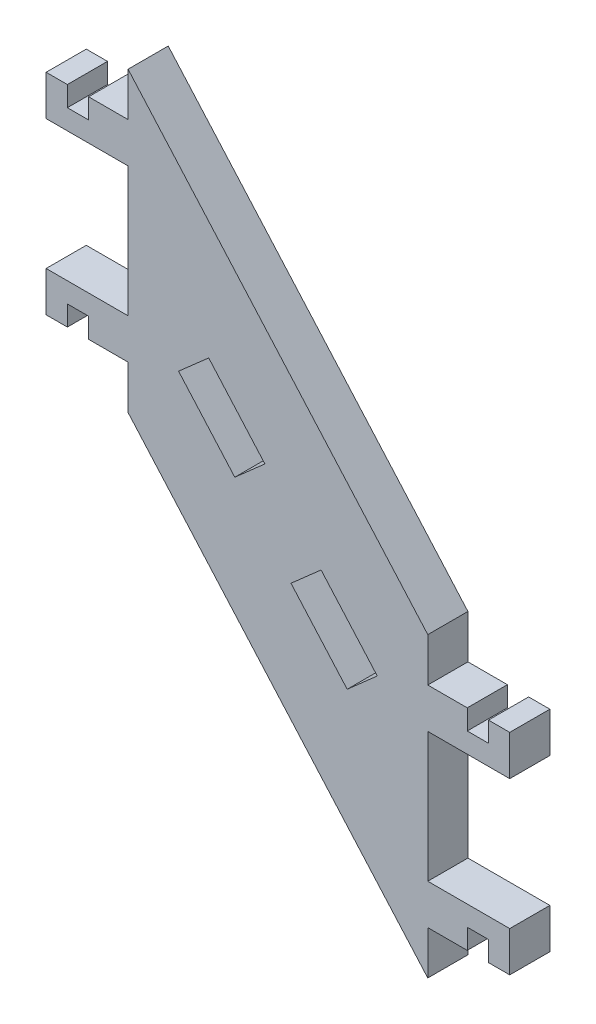
SolidWorks part; units mm, degrees
ref_plane "Front Plane" through (0, 0, 0) normal (0, 0, 1) x (1, 0, 0)
ref_plane "Top Plane" through (0, 0, 0) normal (0, 1, 0) x (1, 0, 0)
ref_plane "Right Plane" through (0, 0, 0) normal (1, 0, 0) x (0, 0, -1)
sketch "Sketch1" plane through (0, 0, 0) normal (0, 0, 1) x (1, 0, 0)
  line L0 (-44.8, 73.025) -> (-44.8, 66.5)
  line L1 (-44.8, 28.575) -> (0, -22.225)
  line L2 (0, -22.225) -> (0, -15.7)
  line L3 (0, 22.225) -> (-44.8, 73.025)
  line L4 (-44.8, 66.5) -> (-50.7, 66.5)
  line L5 (-57.05, 66.5) -> (-57.05, 60.5)
  line L6 (-57.05, 60.5) -> (-44.8, 60.5)
  line L7 (-44.8, 73.025) -> (-50.7, 73.025) construction
  line L8 (-50.7, 73.025) -> (-50.7, 28.575) construction
  line L9 (-50.7, 28.575) -> (-44.8, 28.575) construction
  line L10 (-53.875, 66.5) -> (-53.875, 63.5)
  line L11 (-53.875, 63.5) -> (-50.7, 63.5)
  line L12 (-50.7, 63.5) -> (-50.7, 66.5)
  line L13 (-53.875, 66.5) -> (-57.05, 66.5)
  line L14 (-44.8, 50.8) -> (-64.1486, 50.8) construction
  line L15 (-44.8, 35.1) -> (-50.7, 35.1)
  line L16 (-57.05, 41.1) -> (-44.8, 41.1)
  line L17 (-53.875, 35.1) -> (-57.05, 35.1)
  line L18 (-50.7, 38.1) -> (-50.7, 35.1)
  line L19 (-53.875, 38.1) -> (-50.7, 38.1)
  line L20 (-53.875, 35.1) -> (-53.875, 38.1)
  line L21 (-57.05, 35.1) -> (-57.05, 41.1)
  line L22 (-57.05, 63.5) -> (-50.7, 63.5) construction
  line L23 (0, 0) -> (19.05, 0) construction
  line L24 (0, 9.7) -> (12.25, 9.7)
  line L25 (12.25, 9.7) -> (12.25, 15.7)
  line L26 (12.25, 15.7) -> (9.075, 15.7)
  line L27 (9.075, 15.7) -> (9.075, 12.7)
  line L28 (9.075, 12.7) -> (5.9, 12.7)
  line L29 (5.9, 12.7) -> (5.9, 15.7)
  line L30 (5.9, 15.7) -> (0, 15.7)
  line L31 (5.9, -15.7) -> (0, -15.7)
  line L32 (5.9, -12.7) -> (5.9, -15.7)
  line L33 (9.075, -12.7) -> (5.9, -12.7)
  line L34 (9.075, -15.7) -> (9.075, -12.7)
  line L35 (12.25, -15.7) -> (9.075, -15.7)
  line L36 (12.25, -9.7) -> (12.25, -15.7)
  line L37 (0, -9.7) -> (12.25, -9.7)
  line L38 (0, 22.225) -> (5.9, 22.225) construction
  line L39 (5.9, 22.225) -> (5.9, -22.225) construction
  line L40 (5.9, -22.225) -> (0, -22.225) construction
  line L41 (-44.8, 35.1) -> (-44.8, 41.1) construction
  line L42 (-44.8, 60.5) -> (-44.8, 41.1)
  line L43 (-44.8, 35.1) -> (-44.8, 28.575)
  line L44 (0, 15.7) -> (0, 22.225)
  line L45 (0, -9.7) -> (0, 9.7)
  line L46 (-50.8, -31.2865) -> (-44.8, -31.2865) construction
  line L47 (-50.8, -31.2865) -> (-50.8, 31.2865) construction
  line L48 (-50.8, 31.2865) -> (-44.8, 31.2865) construction
  line L49 (-44.8, -31.2865) -> (-44.8, 31.2865) construction
  line L50 (-50.8, -31.2865) -> (-44.8, 31.2865) construction
  line L51 (-50.8, 31.2865) -> (-44.8, -31.2865) construction
  line L52 (0, -31.2865) -> (6, -31.2865) construction
  line L53 (0, -31.2865) -> (0, 31.2865) construction
  line L54 (0, 31.2865) -> (6, 31.2865) construction
  line L55 (6, -31.2865) -> (6, 31.2865) construction
  line L56 (0, -31.2865) -> (6, 31.2865) construction
  line L57 (0, 31.2865) -> (6, -31.2865) construction
  line L58 (-44.8, 60.5) -> (-44.8, 66.5) construction
  point P25 (-47.8, 0)
  point P37 (0, 0)
  point P53 (3, 0)
  point P58 (-44.8, 38.1)
  point P59 (-44.8, 63.5)
  point P60 (12.25, 12.7)
  point P61 (12.25, -12.7)
  dimension "D4" = 5.9
  dimension "D5" = 3.175
  dimension "D6" = 6
  dimension "D8" = 44.45
  dimension "D10" = 6
  dimension "D11" = 5.9
  dimension "D12" = 3.175
  dimension "D13" = 31.4
  dimension "D14" = 3.175
  dimension "D9" = 3.175
  dimension "D18" = 3.175
  dimension "D19" = 6
  dimension "D20" = 6
  dimension "D21" = 50.8
  dimension "D7" = 25.4
  dimension "D3" = 25.4
  dimension "D15" = 3
  dimension "D16" = 3
  dimension "D17" = 50.8
extrude "Profile" add sketch "Sketch1" along normal blind 6 contours L1 L2 L31 L32 L33 L34 L35 L36 L37 L45 L24 L25 L26 L27 L28 L29 L30 L44 L3 L0 L4 L12 L11 L10 L13 L5 L6 L42 L16 L21 L17 L20 L19 L18 L15 L43
sketch "Sketch2" plane through (0, 0, 6) normal (0, 0, 1) x (1, 0, 0)
  line L0 (-44.8, 50.8) -> (0, 0) construction
  line L1 (-44.8, 60.5) -> (-44.8, 41.1) construction
  line L2 (-32.7501, 41.672) -> (-37.2502, 37.7034)
  line L3 (-37.2502, 37.7034) -> (-28.8501, 28.1783)
  line L4 (-28.8501, 28.1783) -> (-24.35, 32.1468)
  line L5 (-24.35, 32.1468) -> (-32.7501, 41.672)
  line L6 (-33.4253, 15.6769) -> (-11.3747, 35.1231) construction
  line L7 (0, 22.225) -> (-44.8, 73.025) construction
  line L8 (-15.9499, 22.6217) -> (-7.5498, 13.0966)
  line L9 (-20.45, 18.6532) -> (-15.9499, 22.6217)
  line L10 (-12.0499, 9.128) -> (-20.45, 18.6532)
  line L11 (-7.5498, 13.0966) -> (-12.0499, 9.128)
  line L12 (-37.2502, 37.7034) -> (-24.35, 32.1468) construction
  point P7 (-35.0002, 39.6877)
  point P14 (-22.4, 25.4)
  point P21 (-30.8001, 34.9251)
  dimension "D1" = 6
  dimension "D2" = 12.7
  dimension "D3" = 12.7
extrude "Cut-Extrude1" cut sketch "Sketch2" against normal through all
equation "\"D10@Sketch1\"=\"D6@Sketch1\""
equation "\"D12@Sketch1\"=\"D5@Sketch1\""
equation "\"D18@Sketch1\"=\"D9@Sketch1\""
equation "\"D4@Sketch1\"=6mm-.1mm"
equation "\"D3@Sketch1\"=\"D7@Sketch1\""
equation "\"D11@Sketch1\"=\"D4@Sketch1\""
equation "\"D15@Sketch1\"=\"D16@Sketch1\""
